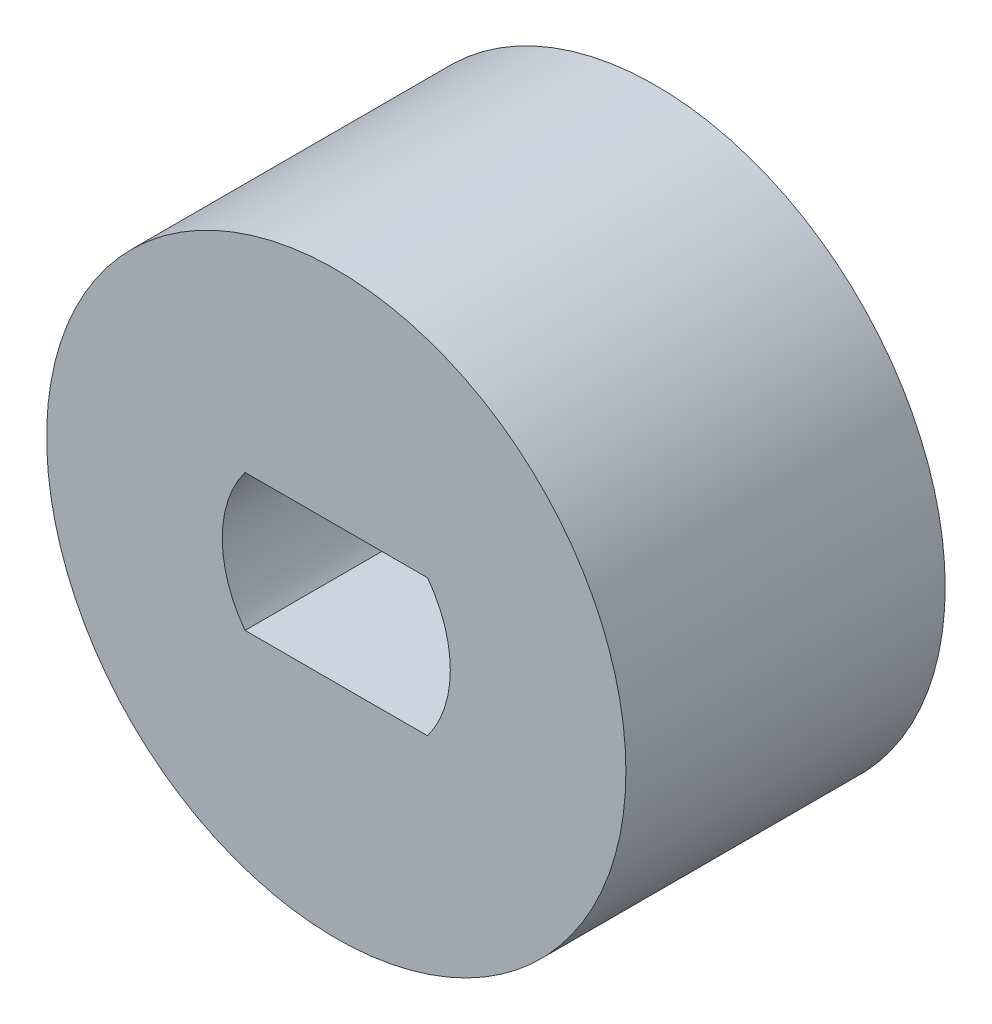
SolidWorks part; units mm, degrees
ref_plane "Front Plane" through (0, 0, 0) normal (0, 0, 1) x (1, 0, 0)
ref_plane "Top Plane" through (0, 0, 0) normal (0, 1, 0) x (1, 0, 0)
ref_plane "Right Plane" through (0, 0, 0) normal (1, 0, 0) x (0, 0, -1)
sketch "Sketch1" plane through (0, 0, 0) normal (0, 0, 1) x (1, 0, 0)
  line L0 (2, 1.5) -> (-2, 1.5)
  line L1 (-2, -1.5) -> (2, -1.5)
  line L2 (-2.5, 0) -> (2.5, 0) construction
  circle A0 centre (0, 0) radius 6.35
  arc A1 (2, -1.5) -> (2, 1.5) centre (0, 0) ccw
  arc A2 (-2, 1.5) -> (-2, -1.5) centre (0, 0) ccw
  dimension "D2" = 2.5
  dimension "D3" = 12.7
  dimension "D1" = 3
extrude "Boss-Extrude1" add sketch "Sketch1" along normal blind 7 contours A0
